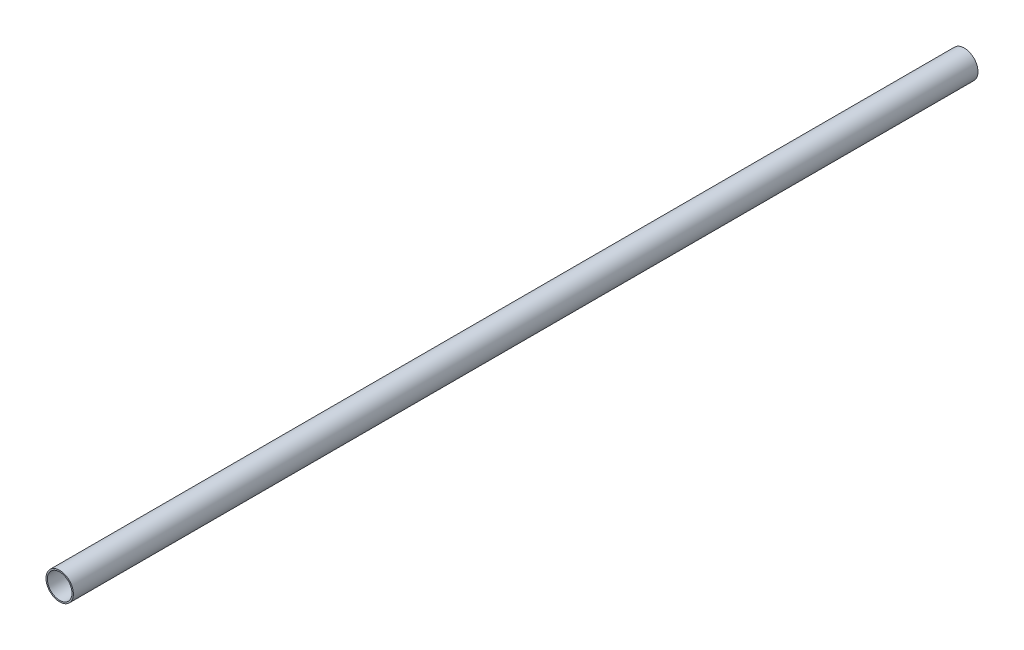
SolidWorks part; units mm, degrees
ref_plane "Ebene vorne" through (0, 0, 0) normal (0, 0, 1) x (1, 0, 0)
ref_plane "Ebene oben" through (0, 0, 0) normal (0, 1, 0) x (1, 0, 0)
ref_plane "Ebene rechts" through (0, 0, 0) normal (1, 0, 0) x (0, 0, -1)
sketch "Skizze1" plane through (0, 0, 0) normal (0, 0, 1) x (1, 0, 0)
  circle A0 centre (0, 0) radius 4.5
  circle A1 centre (0, 0) radius 5
  dimension "D1" = 9
  dimension "D2" = 10
extrude "Aufsatz-Linear austragen1" add sketch "Skizze1" along normal blind 330
